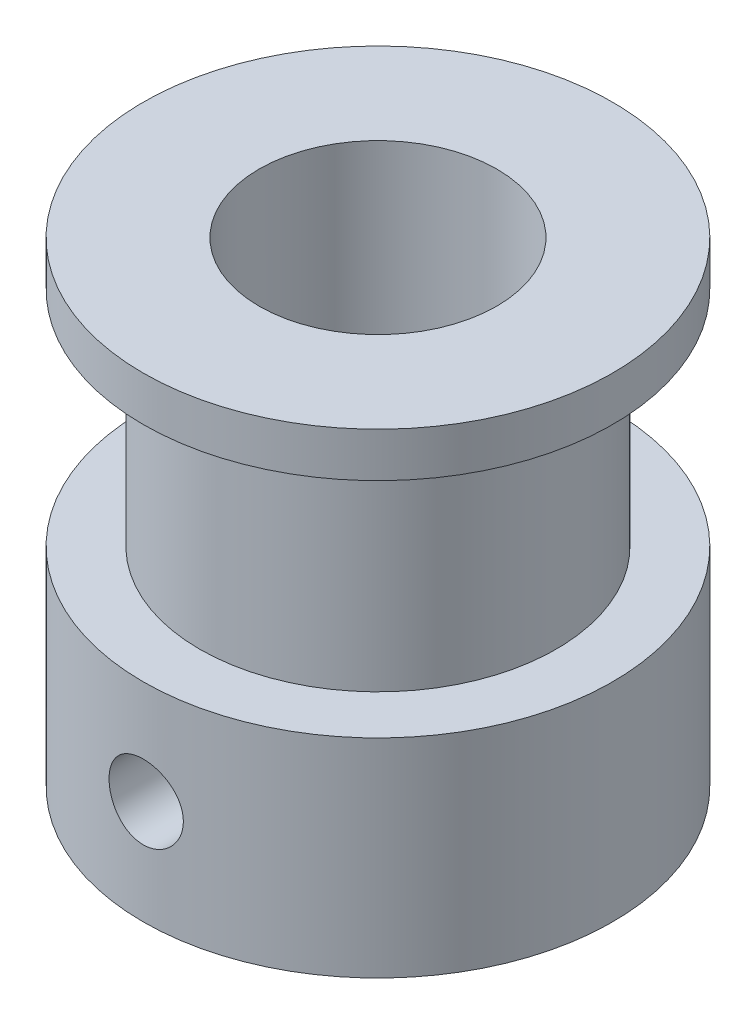
SolidWorks part; units mm, degrees
material "aluminio"
ref_plane "Alzado" through (0, 0, 0) normal (0, 0, 1) x (1, 0, 0)
ref_plane "Planta" through (0, 0, 0) normal (0, 1, 0) x (1, 0, 0)
ref_plane "Vista lateral" through (0, 0, 0) normal (1, 0, 0) x (0, 0, -1)
sketch "Croquis1" plane through (0, 0, 0) normal (0, 1, 0) x (1, 0, 0)
  circle A0 centre (0, 0) radius 7.9
  dimension "D1" = 15.8
extrude "Saliente-Extruir1" add sketch "Croquis1" along normal blind 7
sketch "Croquis2" plane through (0, 7, 0) normal (0, 1, 0) x (1, 0, 0)
  circle A0 centre (0, 0) radius 6
  dimension "D1" = 12
extrude "Saliente-Extruir2" add sketch "Croquis2" along normal blind 7.5
sketch "Croquis3" plane through (0, 14.5, 0) normal (0, 1, 0) x (1, 0, 0)
  circle A0 centre (0, 0) radius 7.9
  circle A1 centre (0, 0) radius 7.9 construction
extrude "Saliente-Extruir3" add sketch "Croquis3" along normal blind 1.5
sketch "Croquis4" plane through (0, 16, 0) normal (0, 1, 0) x (1, 0, 0)
  circle A0 centre (0, 0) radius 4
  dimension "D1" = 8
extrude "Cortar-Extruir1" cut sketch "Croquis4" against normal through all
hole_wizard "Taladro roscado M31 (definir posicio)" positions "Croquis6" profile "Croquis5" tap size "M3" standard "Iso"
sketch "Croquis6" plane through (0, 0, 0) normal (0, 0, 1) x (1, 0, 0)
  line L0 (0, 7) -> (0, 0) construction
  line L1 (7.9, 7) -> (-7.9, 7) construction
  point P0 (0, 3.5)
sketch "Croquis5" plane through (0, 3.5, 0) normal (1, 0, 0) x (0, 1, 0)
  line L0 (0, 0) -> (0, 7.901)
  line L1 (0, 7.901) -> (1.25, 7.901)
  line L2 (1.25, 7.901) -> (1.25, 0)
  line L5 (1.25, 0) -> (0, 0)
  line L11 (0, -6.35) -> (0, 107.95) construction
  dimension "Diámetro de perforador para roscar hasta el siguiente" = 2.5
  dimension "Profundidad de perforador para roscar hasta el siguiente" = 7.901
cosmetic thread "Rosca de taladro1" parameters "D2"=3
cosmetic thread "Rosca cosmética1" parameters "D2"=3
pattern_circular "MatrizC1" count 2 over 90 about axis through (0, 7, 0) along (0, -1, 0) of "Taladro roscado M31 (definir posicio)"
cosmetic thread "Rosca cosmética2" parameters "D2"=3
